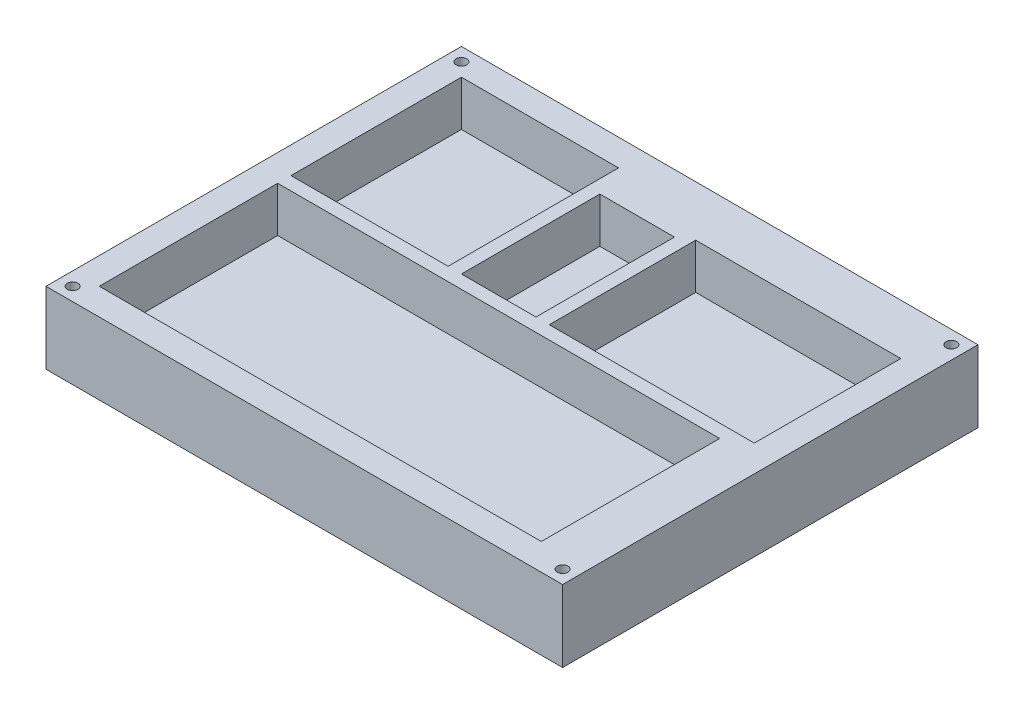
SolidWorks part; units mm, degrees
ref_plane "Front Plane" through (0, 0, 0) normal (0, 0, 1) x (1, 0, 0)
ref_plane "Top Plane" through (0, 0, 0) normal (0, 1, 0) x (1, 0, 0)
ref_plane "Right Plane" through (0, 0, 0) normal (1, 0, 0) x (0, 0, -1)
sketch "Sketch1" plane through (0, 0, 0) normal (0, 1, 0) x (1, 0, 0)
  line L1 (-83, 33.5) -> (83, 33.5)
  line L2 (-83, 33.5) -> (-83, -33.5)
  line L3 (-83, -33.5) -> (83, -33.5)
  line L4 (83, 33.5) -> (83, -33.5)
  line L5 (-83, 33.5) -> (83, -33.5) construction
  line L6 (-83, -33.5) -> (83, 33.5) construction
  line L11 (-88.4365, -38.5) -> (88.4365, 38.5) construction
  line L12 (-88.4365, 38.5) -> (88.4365, -38.5) construction
  line L29 (-83, 38.5) -> (-24, 38.5)
  line L30 (-83, 38.5) -> (-83, 102.5)
  line L31 (-83, 102.5) -> (-24, 102.5)
  line L32 (-24, 38.5) -> (-24, 102.5)
  line L33 (-19, 38.5) -> (9, 38.5)
  line L34 (-19, 38.5) -> (-19, 90.5)
  line L35 (-19, 90.5) -> (9, 90.5)
  line L36 (9, 38.5) -> (9, 90.5)
  line L41 (14, 38.5) -> (91, 38.5)
  line L42 (14, 38.5) -> (14, 93.5)
  line L43 (14, 93.5) -> (91, 93.5)
  line L44 (91, 38.5) -> (91, 93.5)
  line L51 (-88.4365, 112.5) -> (-93, 112.5)
  line L52 (-93, 107.5) -> (-93, 112.5)
  line L53 (-93, 112.5) -> (101, 112.5)
  line L54 (-93, 112.5) -> (-93, -43.5)
  line L55 (-93, -43.5) -> (101, -43.5)
  line L56 (101, 112.5) -> (101, -43.5)
  point P0 (0, 0)
  point P6 (0, 0)
extrude "Boss-Extrude1" add sketch "Sketch1" along normal blind 17
sketch "Sketch2" plane through (0, 0, 0) normal (0, -1, 0) x (-1, 0, 0)
  line L1 (93, -43.5) -> (-101, -43.5)
  line L2 (93, -43.5) -> (93, 112.5)
  line L3 (93, 112.5) -> (-101, 112.5)
  line L4 (-101, -43.5) -> (-101, 112.5)
extrude "Boss-Extrude2" add sketch "Sketch2" along normal blind 10
sketch "Sketch3" plane through (0, -10, 0) normal (0, -1, 0) x (-1, 0, 0)
  circle A20 centre (88, -38.5) radius 2
  circle A25 centre (88, 107.5) radius 2
  circle A29 centre (-96, -38.5) radius 2
  circle A33 centre (-96, 107.5) radius 2
extrude "Cut-Extrude1" cut sketch "Sketch3" against normal blind 30
